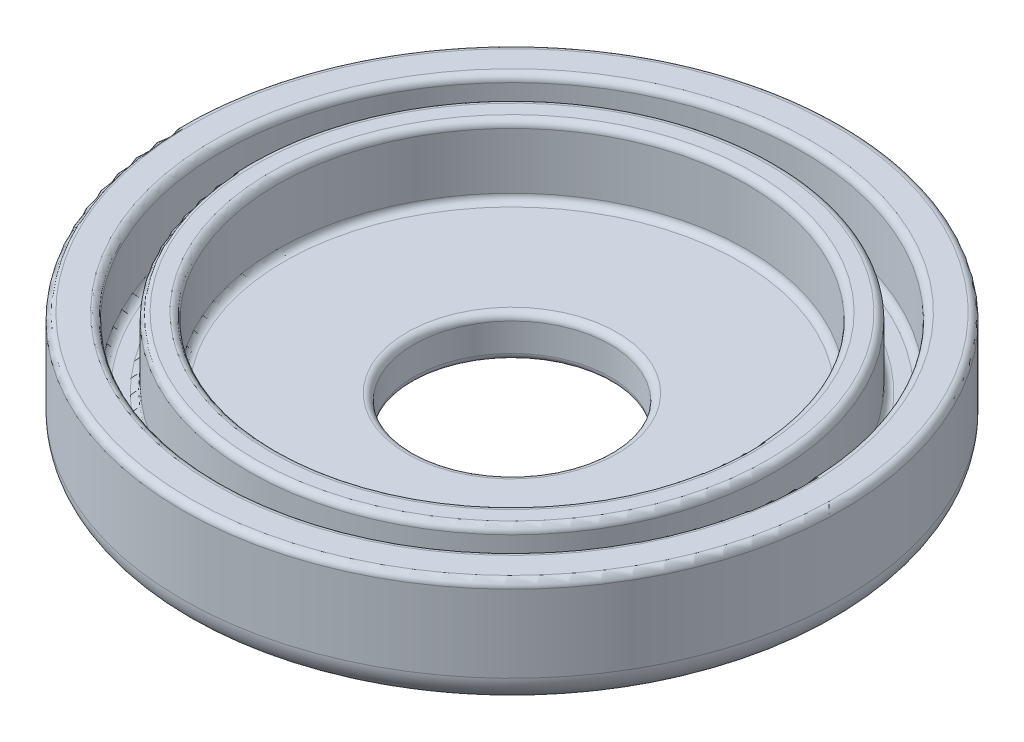
SolidWorks part; units mm, degrees
ref_plane "Front Plane" through (0, 0, 0) normal (0, 0, 1) x (1, 0, 0)
ref_plane "Top Plane" through (0, 0, 0) normal (0, 1, 0) x (1, 0, 0)
ref_plane "Right Plane" through (0, 0, 0) normal (1, 0, 0) x (0, 0, -1)
sketch "Sketch1" plane through (0, 0, 0) normal (0, 1, 0) x (1, 0, 0)
  circle A0 centre (0, 0) radius 23.5
  dimension "D1" = 47
extrude "Boss-Extrude1" add sketch "Sketch1" along normal blind 8
sketch "Sketch2" plane through (0, 8, 0) normal (0, 1, 0) x (1, 0, 0)
  circle A0 centre (0, 0) radius 20.75
  dimension "D1" = 41.5
extrude "Cut-Extrude1" cut sketch "Sketch2" against normal blind 5 contours A0
sketch "Sketch3" plane through (0, 3, 0) normal (0, 1, 0) x (1, 0, 0)
  circle A0 centre (0, 0) radius 18.75
  dimension "D1" = 37.5
extrude "Boss-Extrude2" add sketch "Sketch3" along normal blind 5
sketch "Sketch4" plane through (0, 8, 0) normal (0, 1, 0) x (1, 0, 0)
  circle A0 centre (0, 0) radius 16.75
  dimension "D1" = 33.5
extrude "Cut-Extrude2" cut sketch "Sketch4" against normal blind 5
sketch "Sketch5" plane through (0, 3, 0) normal (0, 1, 0) x (1, 0, 0)
  circle A0 centre (0, 0) radius 7
  dimension "D1" = 14
extrude "Cut-Extrude3" cut sketch "Sketch5" against normal blind 5
fillet "Fillet2" radius 0.5
fillet "Fillet3" radius 2
